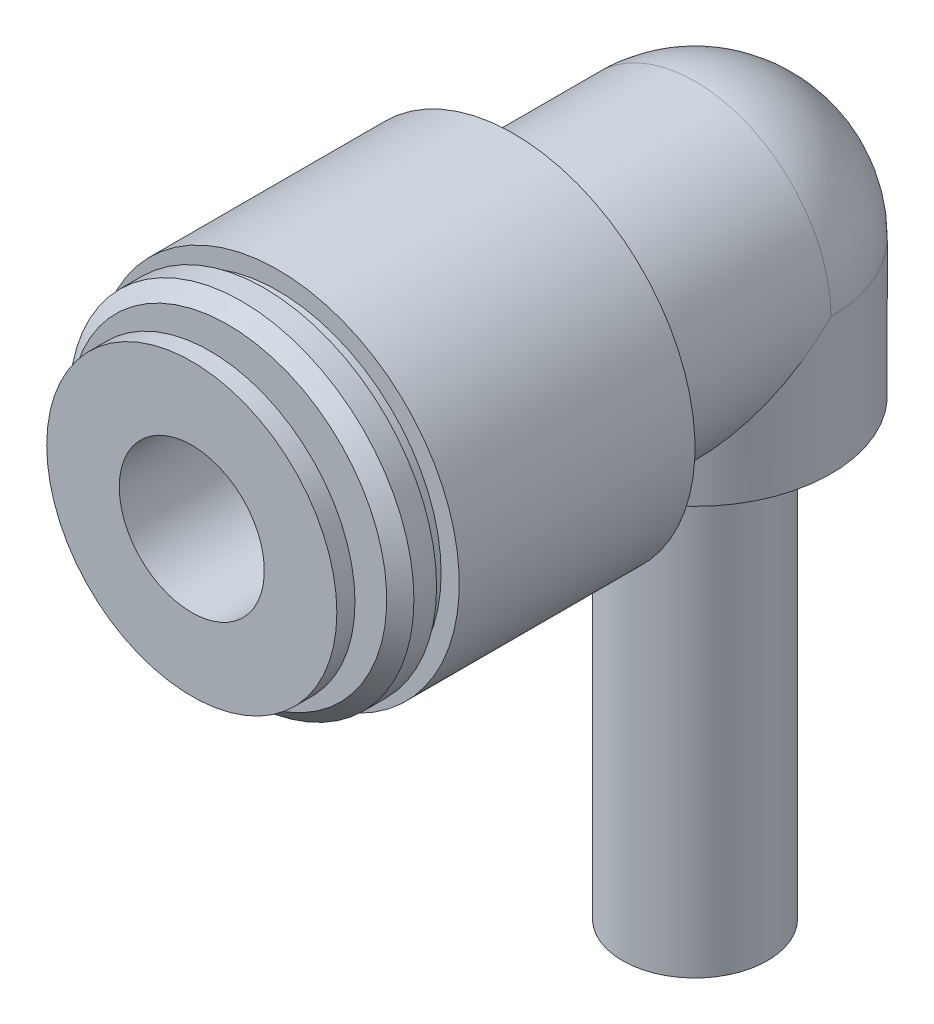
SolidWorks part; units mm, degrees
ref_plane "Спереди" through (0, 0, 0) normal (0, 0, 1) x (1, 0, 0)
ref_plane "Сверху" through (0, 0, 0) normal (0, 1, 0) x (1, 0, 0)
ref_plane "Справа" through (0, 0, 0) normal (1, 0, 0) x (0, 0, -1)
sketch "Эскиз1" plane through (0, 0, 0) normal (0, 1, 0) x (1, 0, 0)
  circle A0 centre (0, 0) radius 4
  circle A1 centre (0, 0) radius 3
  dimension "D1" = 6
  dimension "D2" = 8
extrude "Бобышка-Вытянуть1" add sketch "Эскиз1" along normal blind 25
sketch "Эскиз2" plane through (0, 0, 0) normal (0, 0, 1) x (1, 0, 0)
  line L0 (0, 25) -> (0, 40)
  line L1 (4, 25) -> (-4, 25) construction
  line L2 (0, 25) -> (7.5, 25)
  line L3 (7.5, 25) -> (7.5, 32.5)
  arc A0 (7.5, 32.5) -> (0, 40) centre (0, 32.5) ccw
revolve "Повернуть1" add sketch "Эскиз2" angle 360 about L0
sketch "Эскиз3" plane through (0, 0, 0) normal (0, 0, 1) x (1, 0, 0)
  circle A1 centre (0, 32.5) radius 7.5
extrude "Бобышка-Вытянуть2" add sketch "Эскиз3" along normal blind 10
sketch "Эскиз4" plane through (0, 0, 10) normal (0, 0, 1) x (1, 0, 0)
  circle A0 centre (0, 32.5) radius 10
extrude "Бобышка-Вытянуть3" add sketch "Эскиз4" along normal blind 13
sketch "Эскиз5" plane through (0, 0, 0) normal (1, 0, 0) x (0, 0, -1)
  line L9 (-26.75, 24.5) -> (-26.75, 26.5)
  line L11 (-27.75, 28.5) -> (-27.75, 24.5)
  line L13 (-27.75, 24.5) -> (-26.75, 24.5)
  line L15 (-25.75, 26.5) -> (-25.75, 23.75)
  line L16 (-25, 23) -> (-23.75, 23)
  line L17 (-25.75, 23.75) -> (-25, 23)
  line L18 (-23.75, 23) -> (-23.75, 23.5)
  line L19 (-23.75, 23.5) -> (-23, 23.5)
  line L20 (-23, 23.5) -> (-23, 28.5)
  line L21 (-27.75, 28.5) -> (-23, 28.5)
  line L22 (-26.75, 26.5) -> (-25.75, 26.5)
  line L23 (-23, 32.5) -> (-33.2854, 32.5) construction
  line L24 (-23, 42.5) -> (-23, 22.5) construction
  point P13 (-25.75, 23)
  dimension "D4" = 0.75
  dimension "D5" = 0.75
  dimension "D6" = 2
revolve "Повернуть3" add sketch "Эскиз5" angle 360 about L23
sketch "Эскиз6" plane through (0, 0, 27.75) normal (0, 0, 1) x (1, 0, 0)
  circle A0 centre (0, 32.5) radius 4
  dimension "D1" = 8
extrude "Вырез-Вытянуть1" cut sketch "Эскиз6" against normal blind 28
